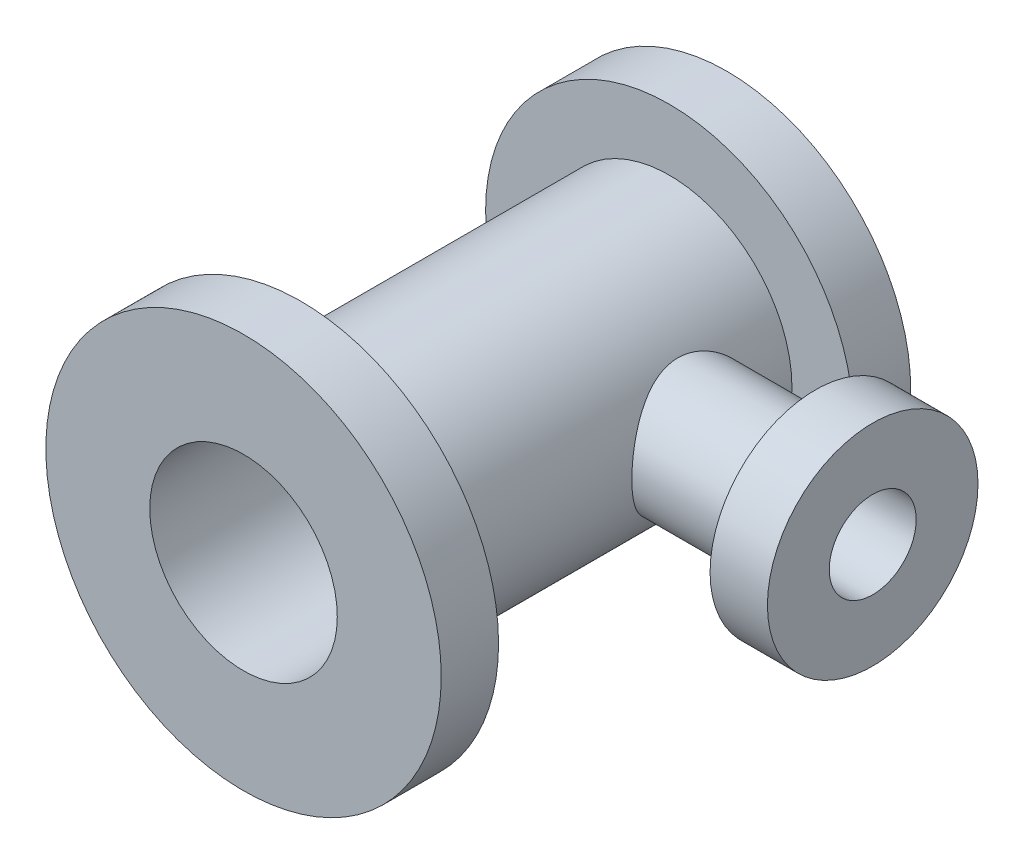
SolidWorks part; units mm, degrees
ref_plane "Front Plane" through (0, 0, 0) normal (0, 0, 1) x (1, 0, 0)
ref_plane "Top Plane" through (0, 0, 0) normal (0, 1, 0) x (1, 0, 0)
ref_plane "Right Plane" through (0, 0, 0) normal (1, 0, 0) x (0, 0, -1)
sketch "Sketch1" plane through (0, 0, 0) normal (0, 0, 1) x (1, 0, 0)
  circle A0 centre (0, 0) radius 22.8922
  circle A1 centre (0, 0) radius 29.8978
extrude "Extrude1" add sketch "Sketch1" along normal blind 113
sketch "Sketch2" plane through (0, 0, 0) normal (1, 0, 0) x (0, 0, -1)
  circle A0 centre (-32.3859, 0) radius 15.7063
  circle A1 centre (-32.3859, 0) radius 10.617
  dimension "D1" = 5.0893
extrude "Extrude2" add sketch "Sketch2" along normal blind 59
sketch "Sketch3" plane through (0, 0, 113) normal (0, 0, 1) x (1, 0, 0)
  circle A0 centre (0, 0) radius 22.8922 construction
  circle A1 centre (0, 0) radius 22.8922
extrude "Cut-Extrude1" cut sketch "Sketch3" against normal blind 222
sketch "Sketch4" plane through (59, 0, 0) normal (1, 0, 0) x (0, 0, -1)
  circle A0 centre (-32.3859, 0) radius 10.617 construction
  circle A1 centre (-32.3859, 0) radius 10.617
extrude "Cut-Extrude2" cut sketch "Sketch4" against normal blind 48
sketch "Sketch5" plane through (0, 0, 113) normal (0, 0, 1) x (1, 0, 0)
  circle A0 centre (0, 0) radius 48.2646
  circle A1 centre (0, 0) radius 29.8978 construction
  circle A2 centre (0, 0) radius 29.8978
extrude "Extrude3" add sketch "Sketch5" against normal blind 14
sketch "Sketch6" plane through (0, 0, 0) normal (0, 0, -1) x (-1, 0, 0)
  circle A1 centre (0, 0) radius 29.8978 construction
  circle A2 centre (0, 0) radius 44.8978
  circle A3 centre (0, 0) radius 44.8978
  circle A4 centre (0, 0) radius 29.8978
  dimension "D1" = 15
extrude "Extrude4" add sketch "Sketch6" against normal blind 9
sketch "Sketch7" plane through (0, 0, 0) normal (0, 0, -1) x (-1, 0, 0)
  circle A0 centre (0, 0) radius 22.8922 construction
  circle A1 centre (0, 0) radius 44.8978
  circle A2 centre (0, 0) radius 44.8978
  circle A3 centre (0, 0) radius 22.8922
  dimension "D1" = 0
extrude "Extrude5" add sketch "Sketch7" along normal blind 5
sketch "Sketch8" plane through (59, 0, 0) normal (1, 0, 0) x (0, 0, -1)
  circle A1 centre (-32.3859, 0) radius 10.617 construction
  circle A2 centre (-32.3859, 0) radius 25.7063
  circle A3 centre (-32.3859, 0) radius 25.7063
  circle A4 centre (-32.3859, 0) radius 10.617
  dimension "D1" = 10
extrude "Extrude6" add sketch "Sketch8" along normal blind 14
